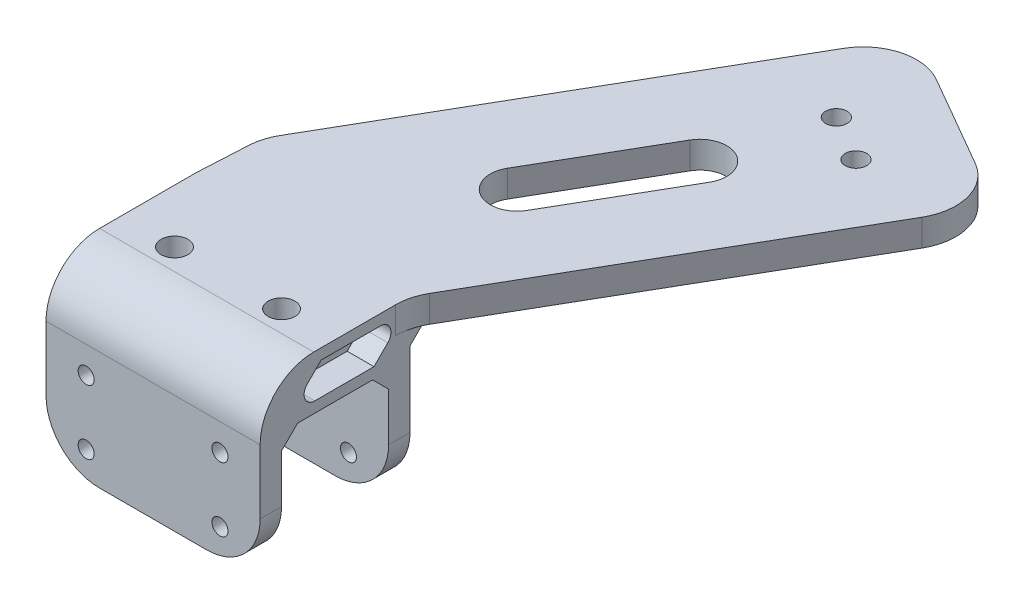
SolidWorks part; units mm, degrees
ref_plane "前视基准面" through (0, 0, 0) normal (0, 0, 1) x (1, 0, 0)
ref_plane "上视基准面" through (0, 0, 0) normal (0, 1, 0) x (1, 0, 0)
ref_plane "右视基准面" through (0, 0, 0) normal (1, 0, 0) x (0, 0, -1)
other "Configuration Table"
sketch "草图1" plane through (0, 0, 0) normal (0, 1, 0) x (1, 0, 0)
  line L1 (20, 14) -> (-20, 14)
  line L2 (20, 14) -> (20, -14)
  line L3 (20, -14) -> (-20, -14)
  line L4 (-20, 14) -> (-20, -14)
  line L5 (20, 14) -> (-20, -14) construction
  line L6 (20, -14) -> (-20, 14) construction
  point P0 (0, 0)
  dimension "D1" = 28
  dimension "D2" = 40
extrude "凸台-拉伸1" add sketch "草图1" along normal blind 10
sketch "草图2" plane through (0, 0, 0) normal (0, -1, 0) x (1, 0, 0)
  line L0 (20, 14) -> (20, -14) construction
  line L1 (-20, 14) -> (20, 14)
  line L2 (-20, 14) -> (-20, 10)
  line L3 (-20, 10) -> (20, 10)
  line L4 (20, 14) -> (20, 10)
  line L5 (-20, -14) -> (-20, 14) construction
  line L6 (-20, -10) -> (20, -10)
  line L7 (-20, -10) -> (-20, -14)
  line L8 (-20, -14) -> (20, -14)
  line L9 (20, -10) -> (20, -14)
  dimension "D1" = 4
  dimension "D2" = 4
extrude "凸台-拉伸2" add sketch "草图2" along normal blind 10
sketch "草图4" plane through (0, 0, -14) normal (0, 0, -1) x (-1, 0, 0)
  line L1 (20, 10) -> (20, -10) construction
  line L2 (-20, 10) -> (20, 10)
  line L3 (-20, 10) -> (-20, 5)
  line L4 (-20, 5) -> (20, 5)
  line L5 (20, 10) -> (20, 5)
  dimension "D1" = 5
extrude "凸台-拉伸3" add sketch "草图4" along normal blind 15
sketch "草图6" plane through (0, 0, -29) normal (0, 0, -1) x (-1, 0, 0)
  line L4 (-20, 10) -> (-20, 5)
  line L5 (-20, 5) -> (20, 5)
  line L6 (20, 5) -> (20, 10)
  line L7 (20, 10) -> (-20, 10)
  line L8 (-20, 10) -> (-20, 5)
  line L9 (-20, 5) -> (20, 5)
  line L10 (20, 5) -> (20, 10)
  line L11 (20, 10) -> (-20, 10)
  dimension "D1" = 0
extrude "凸台-拉伸4" add sketch "草图6" along normal blind 15
sketch "草图7" plane through (0, 5, 0) normal (0, -1, 0) x (1, 0, 0)
  line L0 (0, -39) -> (0, -24) construction
  line L1 (-3.15, -39) -> (-3.15, -24)
  line L2 (3.15, -39) -> (3.15, -24)
  line L3 (20, -44) -> (-20, -44) construction
  arc A0 (-3.15, -39) -> (3.15, -39) centre (0, -39) ccw
  arc A1 (3.15, -24) -> (-3.15, -24) centre (0, -24) ccw
  point P2 (0, -31.5)
  dimension "D1" = 6.3
  dimension "D2" = 15
  dimension "D3" = 5
sketch "草图8" plane through (0, 10, 0) normal (0, 1, 0) x (1, 0, 0)
  line L0 (-20, -14) -> (20, -14) construction
  line L1 (20, -14) -> (20, 44) construction
  line L2 (-20, 44) -> (-20, -14) construction
  circle A0 centre (-10, 0) radius 2.5
  circle A1 centre (10, 0) radius 2.5
  dimension "D1" = 5
  dimension "D3" = 14
  dimension "D4" = 10
  dimension "D5" = 10
  dimension "D2" = 14
extrude "切除-拉伸2" cut sketch "草图8" against normal blind 15
chamfer "倒角1" distance 3 angle 45 2 edges at (0, 0, 10) (0, 0, -10)
fillet "圆角1" radius 10 1 edges at (0, 10, 14)
chamfer "倒角2" distance 3 angle 45 1 edges at (0, 5, -14)
sketch "草图9" plane through (0, 0, -14) normal (0, 0, -1) x (-1, 0, 0)
  line L0 (20, -10) -> (-20, -10) construction
  line L1 (20, 2) -> (20, -10) construction
  line L2 (-20, 2) -> (-20, -10) construction
  circle A0 centre (-12.5, -5) radius 1.5
  circle A1 centre (12.5, -5) radius 1.5
  dimension "D1" = 5
  dimension "D2" = 5
  dimension "D3" = 7.5
  dimension "D4" = 7.5
  dimension "D5" = 3
extrude "切除-拉伸3" cut sketch "草图9" against normal through all
sketch "草图10" plane through (20, 0, 0) normal (1, 0, 0) x (0, 0, -1)
  line L0 (-2.6185, 8) -> (-8.6185, 2)
  line L1 (-8.6185, 2) -> (7.2641, 2)
  line L2 (7.2641, 2) -> (13.2641, 8)
  line L3 (13.2641, 8) -> (-2.6185, 8)
  line L4 (-7, 0) -> (7, 0) construction
  line L5 (-4, 10) -> (44, 10) construction
  line L6 (-10, -3) -> (-7, 0) construction
  dimension "D1" = 2
  dimension "D2" = 2
extrude "切除-拉伸4" cut sketch "草图10" against normal blind 5
fillet "圆角3" radius 2 2 edges at (17.5, 8, -13.2641) (17.5, 2, 8.6185)
ref_plane "基准面1" through (0, 0, 0) normal (1, 0, 0) x (0, 0, -1)
mirror "镜向1" about plane through (0, 0, 0) normal (1, 0, 0) of "切除-拉伸4"
sketch "草图11" plane through (0, -10, 0) normal (0, -1, 0) x (1, 0, 0)
  line L0 (20, 14) -> (-20, 14) construction
  line L1 (-20, -14) -> (20, -14)
  line L2 (-20, -14) -> (-20, -7)
  line L3 (-20, -7) -> (20, -7)
  line L4 (20, -14) -> (20, -7)
  line L5 (-20, 14) -> (20, 14)
  line L6 (-20, 14) -> (-20, 7)
  line L7 (-20, 7) -> (20, 7)
  line L8 (20, 14) -> (20, 7)
  dimension "D1" = 7
  dimension "D2" = 7
extrude "凸台-拉伸5" add sketch "草图11" against normal blind 3 contours L2 L1 L4 L3 | L6 L5 L8 L7
chamfer "倒角3" distance 1 angle 45 2 edges at (0, -7, -7) (0, -7, 7)
sketch "草图12" plane through (0, 0, -44) normal (0, 0, -1) x (-1, 0, 0)
  line L1 (-20, 10) -> (20, 10)
  line L2 (-20, 10) -> (-20, 5)
  line L3 (-20, 5) -> (20, 5)
  line L4 (20, 10) -> (20, 5)
extrude "凸台-拉伸6" add sketch "草图12" along normal blind 30
fillet "圆角4" radius 10 2 edges at (-20, 7.5, -74) (20, 7.5, -74)
sketch "草图13" plane through (0, 10, 0) normal (0, 1, 0) x (1, 0, 0)
  line L0 (20, -4) -> (20, 64) construction
  line L1 (-10, 74) -> (10, 74) construction
  circle A0 centre (9.14, 70) radius 2
  circle A1 centre (-0.86, 70) radius 2
  dimension "D1" = 4
  dimension "D2" = 10.86
  dimension "D3" = 10
  dimension "D4" = 4
  dimension "D5" = 4
extrude "切除-拉伸5" cut sketch "草图13" against normal blind 30
sketch "草图14" plane through (0, 10, 0) normal (0, 1, 0) x (1, 0, 0)
  line L0 (-20, 14) -> (-73.9448, 14) construction
  line L1 (-20, 14) -> (-55, 74.6218)
  line L2 (-20.359, 94.6218) -> (-55, 74.6218)
  line L3 (-20.359, 94.6218) -> (20, 24.718)
  line L4 (-20, 14) -> (-20, 7)
  line L5 (20, 14) -> (-20, 14)
  line L6 (20, 7) -> (20, 14)
  line L7 (-20, 7) -> (20, 7)
  line L8 (-20, 14) -> (-20, 7)
  line L9 (20, 14) -> (-20, 14)
  line L10 (20, 7) -> (20, 14)
  line L11 (-20, 7) -> (20, 7)
  line L12 (20, -4) -> (20, 64) construction
  line L13 (20, 24.718) -> (20, 14)
  line M13 (10, 74) -> (-10, 74)
  arc M14 (-10, 74) -> (-20, 64) centre (-10, 64) ccw
  line M15 (-20, 64) -> (-20, -4)
  line M17 (20, -4) -> (20, 64)
  dimension "D2" = 60
  dimension "D3" = 40
  dimension "D4" = 90
  dimension "D5" = 70
  dimension "D1" = 0
extrude "凸台-拉伸7" add sketch "草图14" against normal blind 5 contours L9 L3 M17 M13 M14 M15 | L3 L2 L1 M15 M14 M13
sketch "草图15" plane through (0, 10, 0) normal (0, 1, 0) x (1, 0, 0)
  line L0 (-8.453, 74) -> (20, 24.718)
  line L1 (20, -4) -> (20, 64) construction
  line L2 (20, 24.718) -> (20, 77.5211)
  line L3 (20, 77.5211) -> (-8.453, 74)
extrude "切除-拉伸6" cut sketch "草图15" against normal blind 5
sketch "草图16" plane through (20, 0, 0) normal (1, 0, 0) x (0, 0, -1)
  line L1 (-10, -7) -> (10, -7)
  line L2 (-10, -7) -> (-10, -16.517)
  line L3 (-10, -16.517) -> (10, -16.517)
  line L4 (10, -7) -> (10, -16.517)
extrude "切除-拉伸7" cut sketch "草图16" against normal through all
sketch "草图17" plane through (0, -10, 0) normal (0, -1, 0) x (1, 0, 0)
  line L1 (-20, -10) -> (20, -10)
  line L2 (-20, -10) -> (-20, -14)
  line L3 (-20, -14) -> (20, -14)
  line L4 (20, -10) -> (20, -14)
  line L5 (-20, 14) -> (20, 14)
  line L6 (-20, 14) -> (-20, 10)
  line L7 (-20, 10) -> (20, 10)
  line L8 (20, 14) -> (20, 10)
extrude "凸台-拉伸8" add sketch "草图17" along normal blind 12
sketch "草图18" plane through (0, 0, 14) normal (0, 0, 1) x (1, 0, 0)
  line L0 (-20, -11) -> (20, -11) construction
  line L1 (-20, 0) -> (-20, -22) construction
  line L2 (20, 0) -> (20, -22) construction
  circle A0 centre (-12.5, -5) radius 1.5 construction
  circle A1 centre (-12.5, -5) radius 1.5
  circle A2 centre (12.5, -5) radius 1.5 construction
  circle A3 centre (12.5, -5) radius 1.5
  circle A4 centre (12.5, -17) radius 1.5
  circle A5 centre (-12.5, -17) radius 1.5
extrude "切除-拉伸8" cut sketch "草图18" against normal through all
sketch "草图19" plane through (0, 10, 0) normal (0, 1, 0) x (1, 0, 0)
  line L0 (-37.6795, 84.6218) -> (-1.9153, 22.6764) construction
  line L1 (-20.359, 94.6218) -> (-55, 74.6218) construction
  circle A0 centre (-30.8494, 82.7917) radius 2
  circle A1 centre (-39.5096, 77.7917) radius 2
  dimension "D1" = 4
  dimension "D2" = 5
  dimension "D3" = 5
extrude "切除-拉伸9" cut sketch "草图19" against normal through all
sketch "草图20" plane through (0, 10, 0) normal (0, 1, 0) x (1, 0, 0)
  line L0 (-37.6795, 84.6218) -> (-3.7712, 25.8908) construction
  line L1 (-20.359, 94.6218) -> (-55, 74.6218) construction
  line L2 (-25.8398, 64.1148) -> (-14.9818, 45.3082) construction
  line L3 (-22.599, 65.9859) -> (-11.741, 47.1793)
  line L4 (-29.0806, 62.2437) -> (-18.2226, 43.4371)
  arc A0 (-22.599, 65.9859) -> (-29.0806, 62.2437) centre (-25.8398, 64.1148) ccw
  arc A1 (-18.2226, 43.4371) -> (-11.741, 47.1793) centre (-14.9818, 45.3082) ccw
  point P6 (-20.4108, 54.7115)
extrude "切除-拉伸10" cut sketch "草图20" against normal through all
sketch "草图22" plane through (0, 10, 0) normal (0, 1, 0) x (1, 0, 0)
  line L0 (20, 14) -> (52.1859, 69.7475)
  line L1 (20, 14) -> (51.1058, 14)
  line L2 (0, 0) -> (0, 93.7297) construction
  line L3 (-20, -4) -> (-20, 24.718)
  line L4 (-20, 14) -> (-20, 10)
  line L5 (20, 14) -> (-20, 14)
  line L6 (20, 10) -> (20, 14)
  line L7 (-20, 10) -> (20, 10)
  line L8 (-20, 14) -> (-20, 10)
  line L9 (20, 14) -> (-20, 14)
  line L10 (20, 10) -> (20, 14)
  line L11 (-20, 10) -> (20, 10)
  line L12 (20.359, 94.6218) -> (55, 74.6218)
  line L13 (-20, 24.718) -> (20.359, 94.6218)
  line L14 (55, 74.6218) -> (20, 14)
  line L17 (20, -4) -> (20, 24.718)
  line L18 (20, 24.718) -> (-20.359, 94.6218)
  line L19 (-20.359, 94.6218) -> (-55, 74.6218)
  line L20 (-55, 74.6218) -> (-20, 14)
  line L21 (-20, 14) -> (-20, -4)
  line L22 (-20, -4) -> (20, -4)
  line L23 (20, -4) -> (20, 24.718)
  line L24 (20, 24.718) -> (-20.359, 94.6218)
  line L25 (-20.359, 94.6218) -> (-55, 74.6218)
  line L26 (-55, 74.6218) -> (-20, 14)
  line L27 (-20, 14) -> (-20, -4)
  line L28 (-20, -4) -> (20, -4)
  line M13 (20, -4) -> (20, 24.718)
  line M14 (20, 24.718) -> (-20.359, 94.6218)
  dimension "D2" = 60
  dimension "D1" = 0
  dimension "D3" = 0
extrude "凸台-拉伸9" add sketch "草图22" against normal blind 5 contours L14 L12 L13 L0 M14 M13
sketch "草图23" plane through (0, 10, 0) normal (0, 1, 0) x (1, 0, 0)
  line L0 (0, 59.359) -> (-23.094, 19.359)
  line L1 (-20, 14) -> (-55, 74.6218) construction
  line L2 (-23.094, 19.359) -> (-20, 14)
  line L3 (-20, 14) -> (-19.3705, 25.8083)
  line L13 (20, -4) -> (20, 14)
  line L14 (20, 14) -> (55, 74.6218)
  line L15 (55, 74.6218) -> (20.359, 94.6218)
  line L16 (20.359, 94.6218) -> (0, 59.359)
  line L17 (0, 59.359) -> (-20.359, 94.6218)
  line L18 (-20.359, 94.6218) -> (-55, 74.6218)
  line L19 (-55, 74.6218) -> (-20, 14)
  line L20 (-20, 14) -> (-20, -4)
  line L21 (-20, -4) -> (20, -4)
  line L22 (20, -4) -> (20, 14)
  line L23 (20, 14) -> (55, 74.6218)
  line L24 (55, 74.6218) -> (20.359, 94.6218)
  line L25 (20.359, 94.6218) -> (0, 59.359)
  line L26 (0, 59.359) -> (-20.359, 94.6218)
  line L27 (-20.359, 94.6218) -> (-55, 74.6218)
  line L28 (-55, 74.6218) -> (-20, 14)
  line L29 (-20, 14) -> (-20, -4)
  line L30 (-20, -4) -> (20, -4)
  line M10 (-18.2226, 43.4371) -> (-29.0806, 62.2437)
  arc M11 (-29.0806, 62.2437) -> (-22.599, 65.9859) centre (-25.8398, 64.1148) cw
  line M12 (-22.599, 65.9859) -> (-11.741, 47.1793)
  arc M13 (-11.741, 47.1793) -> (-18.2226, 43.4371) centre (-14.9818, 45.3082) cw
  circle M14 centre (-30.8494, 82.7917) radius 2
  circle M15 centre (-39.5096, 77.7917) radius 2
  line M20 (0, 59.359) -> (-20.359, 94.6218)
  line M21 (-20.359, 94.6218) -> (-55, 74.6218)
  line M22 (-55, 74.6218) -> (-20, 14)
  dimension "D1" = 0
extrude "切除-拉伸11" cut sketch "草图23" against normal through all contours L0 M20 M21 M22 M15 M14 M13 M10 M11 M12 | L3 L0 M22
sketch "草图24" plane through (0, 10, 0) normal (0, 1, 0) x (1, 0, 0)
  line L0 (37.6795, 84.6218) -> (18.8929, 52.0825) construction
  line L1 (20.359, 94.6218) -> (55, 74.6218) construction
  circle A0 centre (30.8494, 82.7917) radius 2
  circle A1 centre (39.5096, 77.7917) radius 2
  dimension "D1" = 4
  dimension "D2" = 5
  dimension "D3" = 10
extrude "切除-拉伸12" cut sketch "草图24" against normal through all
sketch "草图25" plane through (0, 10, 0) normal (0, 1, 0) x (1, 0, 0)
  line L0 (37.6795, 84.6218) -> (9.7402, 36.2295) construction
  line L1 (20.359, 94.6218) -> (55, 74.6218) construction
  line L2 (12.6795, 41.3205) -> (25.1795, 62.9711) construction
  line L3 (8.3494, 43.8205) -> (20.8494, 65.4711)
  line L4 (17.0096, 38.8205) -> (29.5096, 60.4711)
  arc A0 (8.3494, 43.8205) -> (17.0096, 38.8205) centre (12.6795, 41.3205) ccw
  arc A1 (29.5096, 60.4711) -> (20.8494, 65.4711) centre (25.1795, 62.9711) ccw
  point P6 (18.9295, 52.1458)
  dimension "D1" = 10
  dimension "D2" = 50
  dimension "D3" = 25
extrude "切除-拉伸13" cut sketch "草图25" against normal through all
sketch "草图26" plane through (46.0622, 0, -79.782) normal (0.5, 0, -0.866) x (-0.866, 0, -0.5)
  line L1 (-10.3205, 10) -> (29.6795, 10)
  line L2 (-10.3205, 10) -> (-10.3205, 5)
  line L3 (-10.3205, 5) -> (29.6795, 5)
  line L4 (29.6795, 10) -> (29.6795, 5)
extrude "凸台-拉伸10" add sketch "草图26" along normal blind 10
fillet "圆角6" radius 10 8 edges at (-20, -22, -12) (-20, -22, 12) (20, -22, 12) (20, -22, -12) (20, 7.5, -14) (-19.3705, 7.5, -25.8083) (25.359, 7.5, -103.282) (60, 7.5, -83.282)
